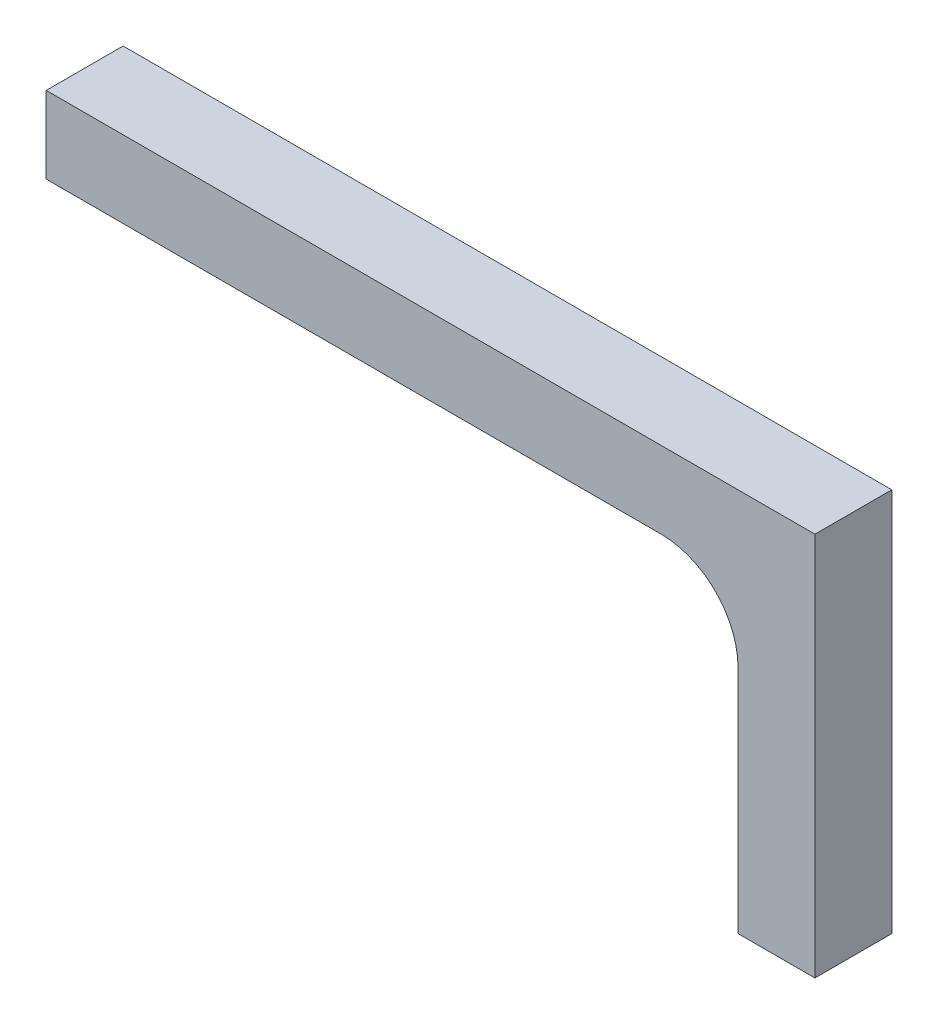
SolidWorks part; units mm, degrees
ref_plane "Plan de face" through (0, 0, 0) normal (0, 0, 1) x (1, 0, 0)
ref_plane "Plan de dessus" through (0, 0, 0) normal (0, 1, 0) x (1, 0, 0)
ref_plane "Plan de droite" through (0, 0, 0) normal (1, 0, 0) x (0, 0, -1)
sketch "Esquisse1" plane through (0, 0, 0) normal (0, 0, 1) x (1, 0, 0)
  line L0 (0, 0) -> (0, 10)
  line L1 (0, 10) -> (100, 10)
  line L2 (100, 10) -> (100, -40)
  line L3 (100, -40) -> (90, -40)
  line L4 (90, -40) -> (90, 0)
  line L5 (90, 0) -> (0, 0)
  dimension "D1" = 100
  dimension "D2" = 50
  dimension "D3" = 10
  dimension "D4" = 10
extrude "Boss.-Extru.1" add sketch "Esquisse1" along normal blind 10
fillet "Congé1" radius 10 1 edges at (90, 0, 5)
equation "\"Length\"= 100'big side of the \"L\""
equation "\"l\"= 50'small side of the \"L\""
equation "\"th\"= 10'thikness"
equation "\"D1@Esquisse1\"=\"Length\""
equation "\"D2@Esquisse1\"=\"l\""
equation "\"D3@Esquisse1\"=\"th\""
equation "\"D4@Esquisse1\"=\"th\""
